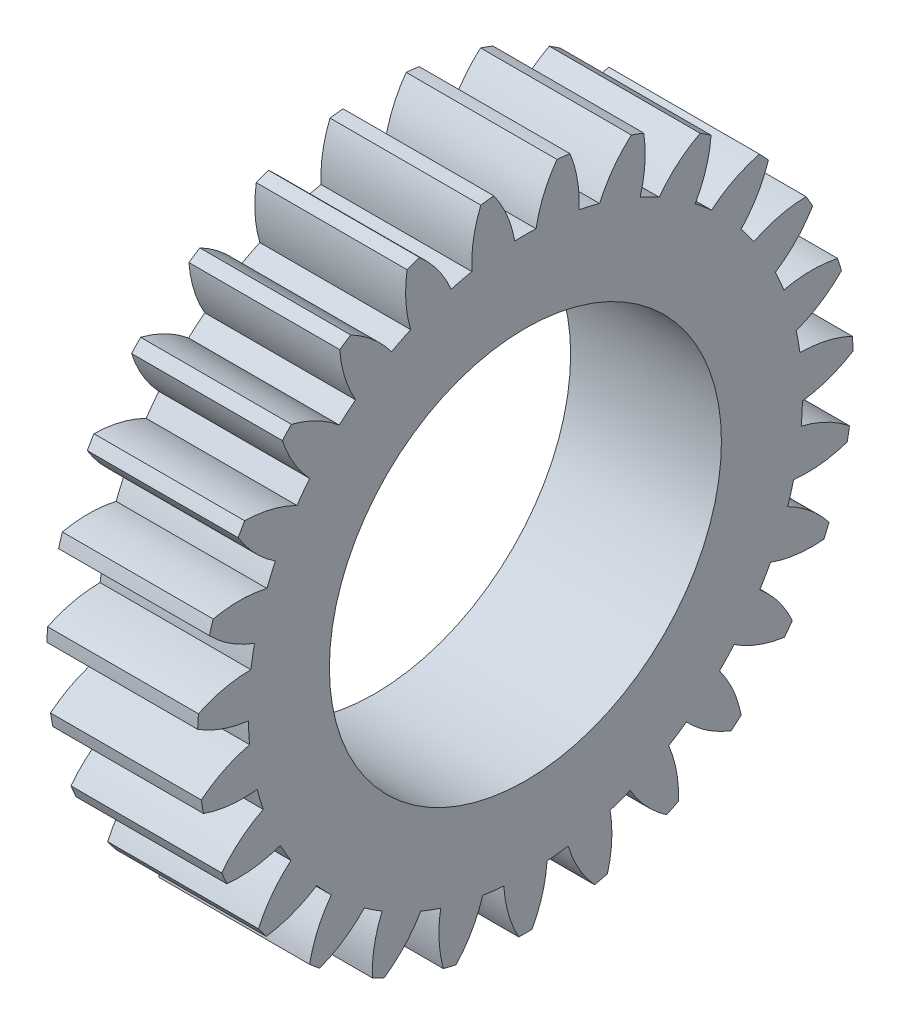
SolidWorks part; units mm, degrees
material "7075-O (SS)"
ref_plane "Plane1" through (0, 0, 0) normal (0, 0, 1) x (1, 0, 0)
ref_plane "Plane2" through (0, 0, 0) normal (0, 1, 0) x (1, 0, 0)
ref_plane "Plane3" through (0, 0, 0) normal (1, 0, 0) x (0, 0, -1)
sketch "HoldingSke" plane through (0, 0, 0) normal (0, 1, 0) x (1, 0, 0)
  line L0 (0, 0) -> (0.594, -0.3027)
  line L1 (-15, 0) -> (100, 0) construction
  line L2 (0, 0) -> (-2.1039, 2.3779)
  line L3 (0, 0) -> (-11.863, 4.5341)
  line L4 (0, 0) -> (7.6947, 3.9207)
  line L5 (0, 0) -> (-46.8476, -17.4728)
  line L6 (0, 0) -> (-8.2896, -5.593)
  line L7 (-2.1039, 2.3779) -> (8.6586, 51.2059)
  line L8 (-76.2, 54.61) -> (-72.9, 54.61)
  line L9 (-71.009, 38.7566) -> (-53.1078, 45.2721)
  line L10 (-76.2, 71.12) -> (104.1128, 71.12)
  line L11 (0, 0) -> (-10, 0)
  line L12 (-76.2, 101.6) -> (-76.147, 101.6)
  line L13 (24.9733, 27.94) -> (52.9518, 28.4284)
  line L14 (24.9733, 27.94) -> (24.9743, 27.94)
  line L15 (24.9733, 27.94) -> (100.4006, 29.5858)
  line L16 (-63.627, -1.5) -> (-12.827, -1.5)
  circle A0 centre (0, 0) radius 13
  circle A1 centre (0, 0) radius 18.374
  circle A2 centre (0, 0) radius 37.5
  circle A3 centre (0, 0) radius 13
  dimension "MHD" = 36.748
  dimension "Hub_dia" = 75
  dimension "Bore" = 26
  dimension "MBD" = 26
  dimension "Num_teeth" = 27
  dimension "Pitch" = 0.6667
  dimension "Overall_len" = 50
  dimension "Show_teeth" = 27
  dimension "Thickness" = 10
  dimension "OAL" = 50.0001
  dimension "T_dim" = 3.3
  dimension "Ap" = 20
  dimension "H" = 19.05
  dimension "Pitch_radius" = 180.3128
  dimension "Width" = 10
  dimension "Backlash" = 0.053
  dimension "Addendum_fac" = 1
  dimension "Dedendum_fac" = 1.25
  dimension "Clearance_fac" = 0.25
  dimension "Dedendum_add" = 0.001
  dimension "Module" = 1.5
sketch "BasProSke" plane through (0, 0, 0) normal (0, 1, 0) x (1, 0, 0)
  line L0 (-10, 0) -> (60, 0) construction
  line L1 (0, 0) -> (0, 21.75)
  line L2 (0, 0) -> (10, 0)
  line L3 (10, 0) -> (10, 21.75)
  line L4 (10, 21.75) -> (0, 21.75)
  dimension "Thickness" = 10
  dimension "Diameter" = 43.5
revolve "Base-Revolve" add sketch "BasProSke" angle 360 about L0
sketch "TooCutSke" plane through (0, 0, 0) normal (1, 0, 0) x (0, 0, -1)
  line L1 (0, 0) -> (0, 107) construction
  line L2 (0, 0) -> (-1.2702, 20.2101) construction
  line L3 (0, 0) -> (-4.695, 40.1684) construction
  line L4 (-1.2702, 20.2101) -> (-2.3475, 20.0842) construction
  arc A0 (0.7048, 18.3605) -> (-0.7048, 18.3605) centre (0, 0) ccw
  arc A1 (2.1089, 21.673) -> (-2.1089, 21.673) centre (0, 0) ccw
  circle A2 centre (0, 0) radius 20.25 construction
  circle A3 centre (0, 0) radius 19.0288 construction
  arc A4 (-0.7048, 18.3605) -> (-2.1089, 21.673) centre (-8.6783, 16.9346) ccw
  arc A5 (2.1089, 21.673) -> (0.7048, 18.3605) centre (8.6783, 16.9346) ccw
  dimension "Root_dia" = 36.748
  dimension "Overcut_dia" = 43.5508
  dimension "Pitch_dia" = 40.5
  dimension "Base_dia" = 38.0576
  dimension "Flank_rad" = 8.1
  dimension "Half_ang" = 6.667
  dimension "Half_CT" = 1.0847
extrude "ToothCut" cut sketch "TooCutSke" along normal through all
fillet "Breaks" [suppressed] radius 0.03
fillet "RootFillets" [suppressed] radius 0.376
pattern_circular "TeethCuts" count 27 every 13.333 about axis through (-10, 0, 0) along (1, 0, 0) of "ToothCut", "RootFillets", "Breaks"
sketch "HubNeaOneSke" plane through (0, 0, 0) normal (-1, 0, 0) x (0, 0, 1)
  circle A0 centre (0, 0) radius 18.374
  dimension "Diameter" = 36.748
extrude "HubNearOne" [suppressed] add sketch "HubNeaOneSke" along normal blind 40.0001
sketch "HubNeaBotSke" plane through (0, 0, 0) normal (-1, 0, 0) x (0, 0, 1)
  circle A0 centre (0, 0) radius 18.374
  dimension "Diameter" = 36.748
extrude "HubNearBoth" [suppressed] add sketch "HubNeaBotSke" along normal blind 20
ref_plane "FarPln" through (10, 0, 0) normal (1, 0, 0) x (0, 0, -1)
sketch "HubFarSke" plane through (10, 0, 0) normal (1, 0, 0) x (0, 0, -1)
  circle A0 centre (0, 0) radius 18.374
  dimension "Diameter" = 36.748
extrude "HubFar" [suppressed] add sketch "HubFarSke" along normal blind 20
sketch "BorSke" plane through (0, 0, 0) normal (1, 0, 0) x (0, 0, -1)
  circle A0 centre (0, 0) radius 13
  dimension "Diameter" = 26
extrude "Bore" cut sketch "BorSke" along normal mid plane 100.0001
sketch "KeySke" plane through (0, 0, 0) normal (1, 0, 0) x (0, 0, -1)
  line L0 (-4, 0) -> (-4, 16.3)
  line L1 (-4, 16.3) -> (4, 16.3)
  line L2 (4, 16.3) -> (4, 0)
  line L3 (0, 0) -> (0, 34) construction
  line L4 (-4, 0) -> (4, 0)
  dimension "Offset" = 16.3
  dimension "Width" = 8
extrude "Keyway" [suppressed] cut sketch "KeySke" along normal mid plane 100.0001
pattern_circular "Keyway2" [suppressed] count 2 every 90 about axis through (-10, 0, 0) along (1, 0, 0)
equation "' \"Module@HoldingSke\" = 6.35"
equation "' \"Num_teeth@HoldingSke\" = 12"
equation "' \"Ap@HoldingSke\" =  20"
equation "' \"Ap@HoldingSke\" = 20"
equation "' \"Width@HoldingSke\" = 0.5 * 25.4"
equation "' \"Hub_dia@HoldingSke\"= 1 * 25.4"
equation "' \"Hub_dia@HoldingSke\" = 1 * 25.4"
equation "' \"Overall_len@HoldingSke\" = 1.0 * 25.4"
equation "' \"Bore@HoldingSke\" = 0.75 * 25.4"
equation "' \"T_dim@HoldingSke\" = 0.1 * 25.4"
equation "' \"Width@KeySke\" = 0.25 * 25.4"
equation "' \"Show_teeth@HoldingSke\" = 13"
equation "' \"Backlash@HoldingSke\" = 0.009 * 25.4"
equation "' \"Addendum_fac@HoldingSke\" = 1.0"
equation "' \"Dedendum_fac@HoldingSke\" = 1.25"
equation "' \"Dedendum_add@HoldingSke\" = 0.00005 * 25.4"
equation "' \"Clearance_fac@HoldingSke\" = 0.25"
equation "\"Pitch@HoldingSke\" = 1 / \"Module@HoldingSke\""
equation "\"Overcut_dia@TooCutSke\" = (\"Num_teeth@HoldingSke\" + 2 * \"Addendum_fac@HoldingSke\") / \"Pitch@HoldingSke\" + 0.002 * 25.4"
equation "\"Pitch_dia@TooCutSke\" = \"Num_teeth@HoldingSke\" / \"Pitch@HoldingSke\""
equation "\"Base_dia@TooCutSke\" = \"Num_teeth@HoldingSke\" / \"Pitch@HoldingSke\" * cos((\"Ap@HoldingSke\"  * 3.14159265 / 180))"
equation "\"Root_dia@TooCutSke\" = (\"Num_teeth@HoldingSke\" + 2) / \"Pitch@HoldingSke\" - 2 * (\"Addendum_fac@HoldingSke\" + \"Dedendum_fac@HoldingSke\") / \"Pitch@HoldingSke\" - \"Dedendum_add@HoldingSke\" * 2"
equation "\"Half_ang@TooCutSke\" = 180 / \"Num_teeth@HoldingSke\""
equation "\"Half_CT@TooCutSke\" = \"Num_teeth@HoldingSke\" / \"Pitch@HoldingSke\" * sin((3.14159265 / 2 / \"Num_teeth@HoldingSke\")) / 2 - 7 * \"Backlash@HoldingSke\" / 4"
equation "\"Flank_rad@TooCutSke\" = \"Num_teeth@HoldingSke\" / \"Pitch@HoldingSke\" / 5"
equation "\"Radius@RootFillets\" = \"Clearance_fac@HoldingSke\" / \"Pitch@HoldingSke\" + \"Dedendum_add@HoldingSke\""
equation "\"Break_rad@Breaks\" = 0.02 / \"Pitch@HoldingSke\""
equation "\"Thickness@HoldingSke\" = \"Width@HoldingSke\""
equation "\"OAL@HoldingSke\" = \"Thickness@HoldingSke\""
equation "\"MHD@HoldingSke\" = (\"Num_teeth@HoldingSke\" + 2) / \"Pitch@HoldingSke\" - 2 * (\"Addendum_fac@HoldingSke\" + \"Dedendum_fac@HoldingSke\")  / \"Pitch@HoldingSke\" - \"Dedendum_add@HoldingSke\" * 2"
equation "\"MBD@HoldingSke\" = (\"Num_teeth@HoldingSke\" + 2) / \"Pitch@HoldingSke\" - 2 * (\"Addendum_fac@HoldingSke\" + \"Dedendum_fac@HoldingSke\")  / \"Pitch@HoldingSke\" - \"Dedendum_add@HoldingSke\" * 2 - 0.002 * 25.4"
equation "\"MHD@HoldingSke\" = ((sgn( \"MHD@HoldingSke\" - \"Hub_dia@HoldingSke\" )-1)*( \"MHD@HoldingSke\" - \"Hub_dia@HoldingSke\" ))/-2+ \"Hub_dia@HoldingSke\""
equation "\"MBD@HoldingSke\" = ((sgn( \"MBD@HoldingSke\" - \"Bore@HoldingSke\" )-1)*( \"MBD@HoldingSke\" - \"Bore@HoldingSke\" ))/-2+ \"Bore@HoldingSke\""
equation "\"OAL@HoldingSke\" = ((sgn( \"OAL@HoldingSke\" - \"Overall_len@HoldingSke\" )+1)*( \"OAL@HoldingSke\" - \"Overall_len@HoldingSke\" ))/2 + \"Overall_len@HoldingSke\" + 0.000002 * 25.4"
equation "\"Num_teeth@TeethCuts\" = int( \"Show_teeth@HoldingSke\" ) + 1"
equation "\"Num_teeth@TeethCuts\" = ((sgn( \"Num_teeth@TeethCuts\" - \"Num_teeth@HoldingSke\" )-1)*( \"Num_teeth@TeethCuts\" - \"Num_teeth@HoldingSke\" ))/-2+ \"Num_teeth@HoldingSke\""
equation "\"Num_teeth@TeethCuts\" = ((sgn( \"Num_teeth@TeethCuts\" - 2.0)+1)*( \"Num_teeth@TeethCuts\" - 2.0))/2 +2.0"
equation "\"Angle@TeethCuts\" = 360.0 / \"Num_teeth@HoldingSke\""
equation "\"Diameter@BasProSke\" = (\"Num_teeth@HoldingSke\" + 2 * \"Addendum_fac@HoldingSke\") / \"Pitch@HoldingSke\""
equation "\"Thickness@BasProSke\"  = \"Thickness@HoldingSke\""
equation "' \"Fillet_rad@BasProSke\" =  \"Thickness@HoldingSke\" * 0.05"
equation "' \"Fillet_rad@BasProSke\" = \"Thickness@HoldingSke\" * 0.05"
equation "\"MHD@HoldingSke\" = ((sgn( \"MHD@HoldingSke\" - \"Root_dia@TooCutSke\" )-1)*( \"MHD@HoldingSke\" - \"Root_dia@TooCutSke\" ))/-2+ \"Root_dia@TooCutSke\""
equation "\"Diameter@HubNeaOneSke\" = \"MHD@HoldingSke\""
equation "\"Length@HubNearOne\" = \"OAL@HoldingSke\" - \"Thickness@BasProSke\""
equation "\"Diameter@HubNeaBotSke\" = \"MHD@HoldingSke\""
equation "\"Length@HubNearBoth\" = ( \"OAL@HoldingSke\" - \"Thickness@BasProSke\" ) / 2.0"
equation "\"Thickness@FarPln\" = \"Thickness@BasProSke\""
equation "\"Diameter@HubFarSke\" = \"MHD@HoldingSke\""
equation "\"Length@HubFar\" = ( \"OAL@HoldingSke\" - \"Thickness@BasProSke\" ) / 2.0"
equation "\"Diameter@BorSke\" = \"MBD@HoldingSke\""
equation "\"D1@Bore\" = \"OAL@HoldingSke\" * 2.0"
equation "\"D1@Keyway\" = \"OAL@HoldingSke\" * 2.0"
equation "\"Offset@KeySke\" = \"T_dim@HoldingSke\" + \"MBD@HoldingSke\" / 2.0"
